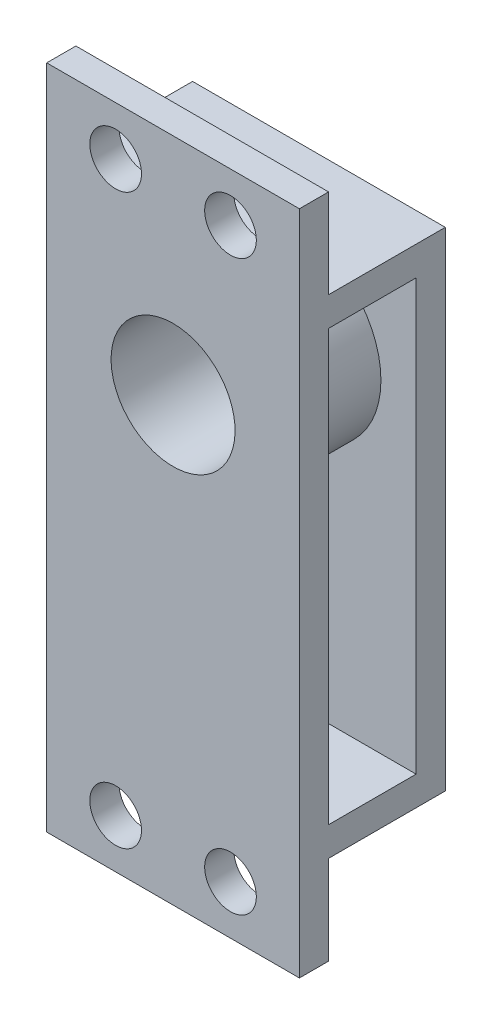
SolidWorks part; units mm, degrees
ref_plane "Front Plane" through (0, 0, 0) normal (0, 0, 1) x (1, 0, 0)
ref_plane "Top Plane" through (0, 0, 0) normal (0, 1, 0) x (1, 0, 0)
ref_plane "Right Plane" through (0, 0, 0) normal (1, 0, 0) x (0, 0, -1)
sketch "Sketch1" plane through (0, 0, 0) normal (0, 0, 1) x (1, 0, 0)
  line L0 (-10.5, -21.25) -> (10.5, -21.25) construction
  line L1 (-11, 29) -> (11, 29)
  line L2 (-11, 29) -> (-11, -29)
  line L3 (-11, -29) -> (11, -29)
  line L4 (11, 29) -> (11, -29)
  line L5 (-11, 29) -> (11, -29) construction
  line L6 (-11, -29) -> (11, 29) construction
  line L7 (-10.5, -21.25) -> (-10.5, 21.25) construction
  line L8 (-10.5, 21.25) -> (10.5, 21.25) construction
  line L9 (10.5, -21.25) -> (10.5, 21.25) construction
  line L10 (-10.5, -21.25) -> (10.5, 21.25) construction
  line L11 (-10.5, 21.25) -> (10.5, -21.25) construction
  line L12 (-5, -24.75) -> (5, -24.75) construction
  line L13 (-5, -24.75) -> (-5, 24.75) construction
  line L14 (-5, 24.75) -> (5, 24.75) construction
  line L15 (5, -24.75) -> (5, 24.75) construction
  line L16 (-5, -24.75) -> (5, 24.75) construction
  line L17 (-5, 24.75) -> (5, -24.75) construction
  line L18 (0, 9.4592) -> (0, 0) construction
  circle A0 centre (-5, -24.75) radius 2.5 construction
  circle A1 centre (5, -24.75) radius 2.5 construction
  circle A2 centre (-5, 24.75) radius 2.5 construction
  circle A3 centre (5, 24.75) radius 2.5 construction
  point P0 (0, 0)
  point P6 (0, 0)
  point P11 (0, 0)
  point P16 (0, 9.4592)
  dimension "D8" = 5
  dimension "D1" = 22
  dimension "D2" = 58
  dimension "D3" = 42.5
  dimension "D4" = 15.2908
  dimension "D5" = 49.5
  dimension "D6" = 21
  dimension "D7" = 10
extrude "Boss-Extrude1" add sketch "Sketch1" along normal blind 2.54
sketch "Sketch6" plane through (-11, 0, 0) normal (-1, 0, 0) x (0, 0, 1)
  line L0 (0, 21.25) -> (-10.16, 21.25)
  line L1 (0, -21.25) -> (0, 21.25) construction
  line L2 (-10.16, 21.25) -> (-10.16, -21.25)
  line L3 (-10.16, -21.25) -> (0, -21.25)
  line L4 (0, 21.25) -> (0, -21.25) construction
  line L5 (0, 29) -> (0, -29) construction
  line L6 (2.54, 29) -> (2.54, -29) construction
  dimension "D1" = 12.7
  dimension "D2" = 42.5
extrude "Extrude-Thin2" add sketch "Sketch6" against normal up to surface (22 mm away) thin up to face at (11, 0, 1.27) thin type one direction reverse wall 2.54
sketch "Sketch7" plane through (0, 0, -10.16) normal (0, 0, -1) x (-1, 0, 0)
  circle A0 centre (0, 9.4592) radius 5.3975
  circle A1 centre (0, 9.4592) radius 7.9375
  dimension "D1" = 10.795
  dimension "D2" = 2.54
extrude "Boss-Extrude2" add sketch "Sketch7" against normal up to surface (10.16 mm away) up to face at (0, 0, 0)
sketch "Sketch8" plane through (0, 0, -10.16) normal (0, 0, -1) x (-1, 0, 0)
  circle A0 centre (0, 9.4592) radius 5.3975 construction
  circle A1 centre (0, 9.4592) radius 5.3975
extrude "Cut-Extrude1" cut sketch "Sketch8" against normal through all
hole_wizard "M4 Clearance Hole1" positions "Sketch9" profile "Sketch10" hole size "M4" standard "ANSI Metric" end condition up to next
sketch "Sketch9" plane through (0, 0, 0) normal (0, 0, -1) x (-1, 0, 0)
  point P0 (-5, 24.75)
  point P3 (5, 24.75)
  point P6 (-5, -24.75)
  point P9 (5, -24.75)
sketch "Sketch10" plane through (5, 24.75, 0) normal (1, 0, 0) x (0, 1, 0)
  line L0 (0, 0) -> (0, 2.54)
  line L1 (0, 2.54) -> (2.25, 2.54)
  line L2 (2.25, 2.54) -> (2.25, 0)
  line L5 (2.25, 0) -> (0, 0)
  line L11 (0, -6.35) -> (0, 107.95) construction
  dimension "Thru Hole Dia." = 4.5
  dimension "Thru Hole Depth" = 2.54
